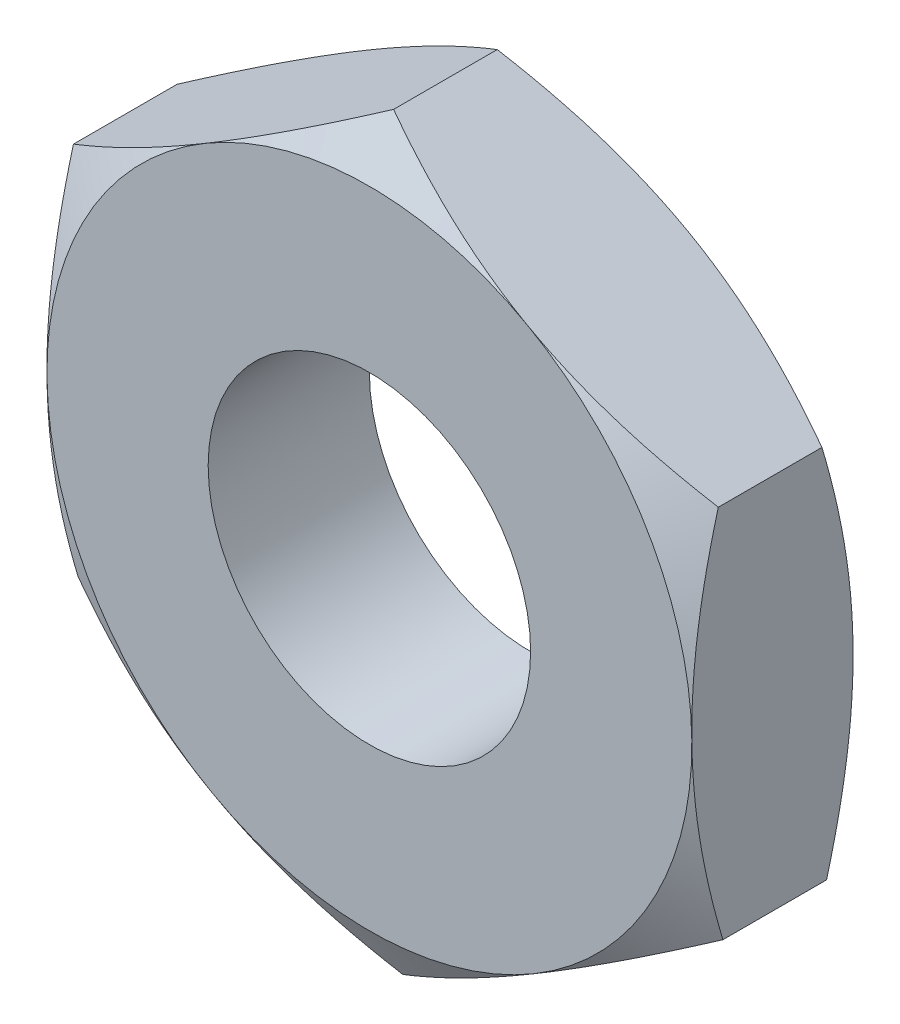
SolidWorks part; units mm, degrees
ref_plane "Front Plane" through (0, 0, 0) normal (0, 0, 1) x (1, 0, 0)
ref_plane "Top Plane" through (0, 0, 0) normal (0, 1, 0) x (1, 0, 0)
ref_plane "Right Plane" through (0, 0, 0) normal (1, 0, 0) x (0, 0, -1)
sketch "Sketch1" plane through (0, 0, 0) normal (0, 0, 1) x (1, 0, 0)
  line L1 (10.0702, -5.6501) -> (9.9282, 5.896)
  line L2 (9.9282, 5.896) -> (-0.142, 11.5461)
  line L3 (-0.142, 11.5461) -> (-10.0702, 5.6501)
  line L4 (-10.0702, 5.6501) -> (-9.9282, -5.896)
  line L5 (-9.9282, -5.896) -> (0.142, -11.5461)
  line L6 (0.142, -11.5461) -> (10.0702, -5.6501)
  circle A0 centre (0, 0) radius 10 construction
  circle A1 centre (0, 0) radius 5
  point P10 (0, 0)
  dimension "D1" = 20
extrude "Boss-Extrude1" add sketch "Sketch1" along normal mid plane 5
sketch "Sketch2" plane through (0, 0, 2.5) normal (0, 0, 1) x (1, 0, 0)
  circle A0 centre (0, 0) radius 10
extrude "Cut-Extrude1" cut sketch "Sketch2" against normal blind 5 draft 60 flip side to cut
mirror "Mirror1" about plane through (0, 0, 0) normal (0, 0, 1) of "Cut-Extrude1"
